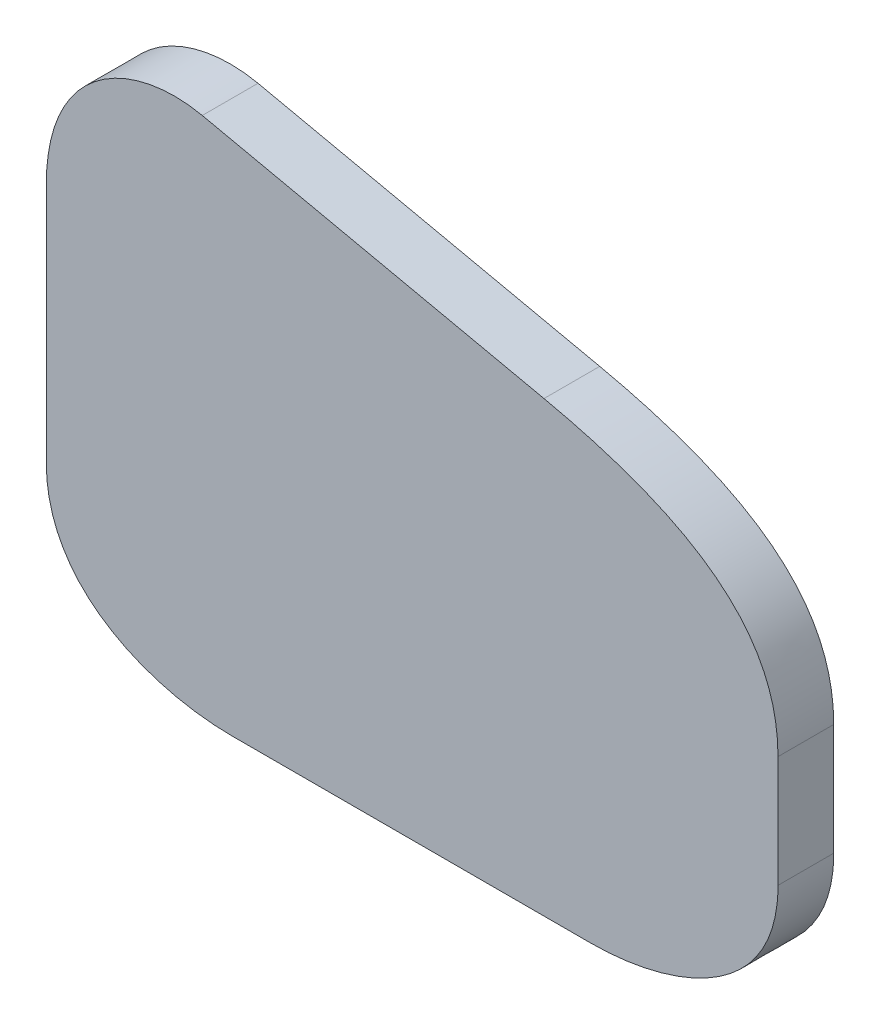
SolidWorks part; units mm, degrees
ref_plane "Спереди" through (0, 0, 0) normal (0, 0, 1) x (1, 0, 0)
ref_plane "Сверху" through (0, 0, 0) normal (0, 1, 0) x (1, 0, 0)
ref_plane "Справа" through (0, 0, 0) normal (1, 0, 0) x (0, 0, -1)
sketch "Эскиз1_fr" plane through (0, 0, 0) normal (0, 0, 1) x (1, 0, 0)
  line L0 (0, 0) -> (0, 20)
  line L1 (-41.9869, 54.6497) -> (-103.3012, 67.9789)
  line L2 (-131.2925, 43.0977) -> (-131.2925, 0)
  line L3 (-33.5451, -25.7698) -> (-97.9695, -25.7698)
  spline S0 degree 3 poles (0, 20) (0, 38.146) (-14.2095, 48.6111) (-41.9869, 54.6497) knots 0 0 0 0 1 1 1 1
  spline S1 degree 3 poles (-103.3012, 67.9789) (-115.5, 70.6308) (-131.2925, 63.3933) (-131.2925, 43.0977) knots 0 0 0 0 1 1 1 1
  spline S2 degree 3 poles (-33.5451, -25.7698) (-19.4449, -25.7698) (0, -19.0638) (0, 0) knots 0 0 0 0 1 1 1 1
  spline S3 degree 3 poles (-97.9695, -25.7698) (-112.0112, -25.7698) (-131.2925, -19.0252) (-131.2925, 0) knots 0 0 0 0 1 1 1 1
  dimension "D1" = 20
extrude "Бобышка-Вытянуть1" add sketch "Эскиз1_fr" along normal blind 10
